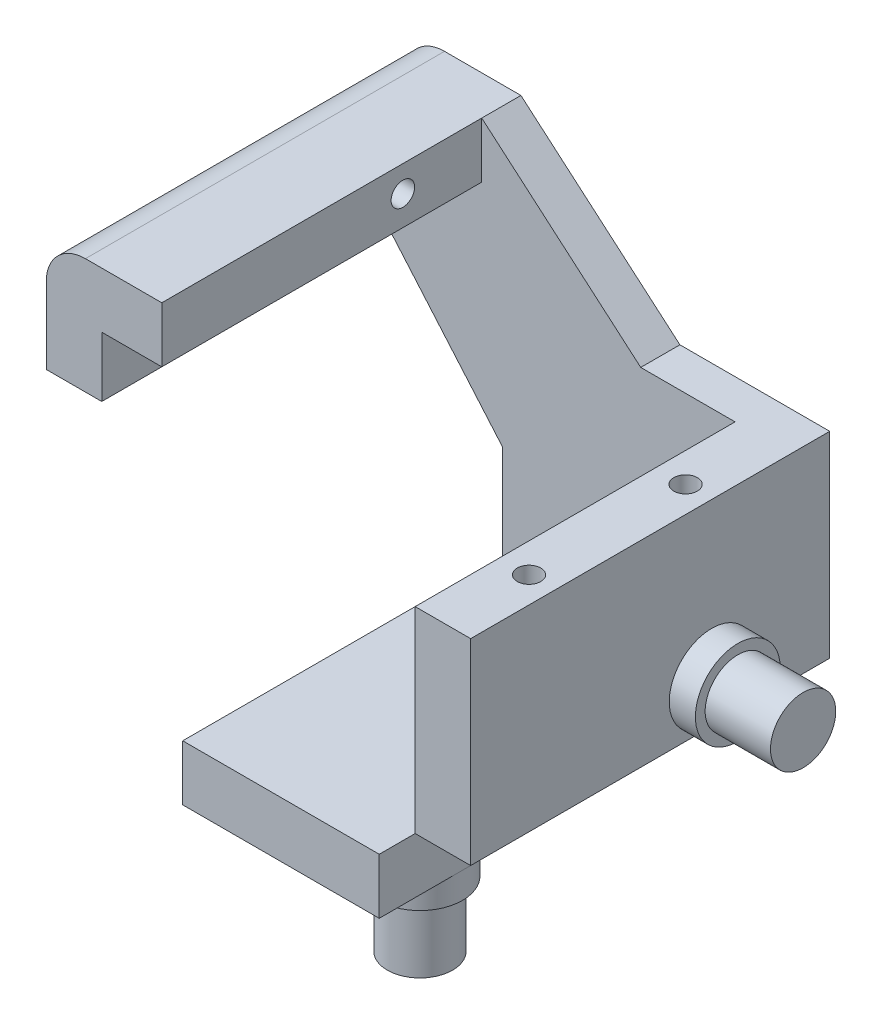
SolidWorks part; units mm, degrees
ref_plane "前视基准面" through (0, 0, 0) normal (0, 0, 1) x (1, 0, 0)
ref_plane "上视基准面" through (0, 0, 0) normal (0, 1, 0) x (1, 0, 0)
ref_plane "右视基准面" through (0, 0, 0) normal (1, 0, 0) x (0, 0, -1)
sketch "草图1" plane through (0, 0, 0) normal (0, 0, 1) x (1, 0, 0)
  line L1 (-16.25, -16.25) -> (16.25, -16.25)
  line L2 (-16.25, -16.25) -> (-16.25, 13.25)
  line L3 (-13.25, 16.25) -> (16.25, 16.25)
  line L4 (16.25, -16.25) -> (16.25, 16.25)
  arc A0 (-13.25, 16.25) -> (-16.25, 13.25) centre (-13.25, 13.25) ccw
  dimension "D1" = 3
extrude "凸台-拉伸1" add sketch "草图1" along normal blind 27.5
sketch "草图3" plane through (0, 0, 27.5) normal (0, 0, 1) x (1, 0, 0)
  line L1 (-12, -12) -> (12, -12)
  line L2 (-12, -12) -> (-12, 12)
  line L3 (-12, 12) -> (12, 12)
  line L4 (12, -12) -> (12, 12)
extrude "切除-拉伸3" cut sketch "草图3" against normal blind 24.5
sketch "草图4" plane through (0, 0, 27.5) normal (0, 0, 1) x (1, 0, 0)
  line L0 (-16.25, 16.25) -> (16.25, -16.25)
  line L1 (16.25, 16.25) -> (-7.4, 16.25)
  line L2 (16.25, 16.25) -> (16.25, 5.8)
  line L3 (16.25, 5.8) -> (-0.175, 5.8)
  line L5 (-7.4, 16.25) -> (-7.4, 12)
  line L7 (12, 12) -> (-12, 12) construction
  line L8 (-7.4, 12) -> (-0.175, 5.8)
extrude "切除-拉伸4" cut sketch "草图4" along direction (0, 0, -1) on the side against the normal blind 24.5 contours L3 L8 L5 L1 L2
ref_plane "基准面3" through (0, 0, 0) normal (0.7071, 0.7071, 0) x (0.7071, -0.7071, 0)
mirror "镜向1" about plane through (0, 0, 0) normal (0.7071, 0.7071, 0) of "切除-拉伸4"
sketch "草图6" plane through (0, 0, 0) normal (0, 0, -1) x (-1, 0, 0)
  line L0 (10.695, 10.695) -> (-10.695, -10.695) construction
  line L1 (-16.25, -16.25) -> (-6, -16.25)
  line L2 (-16.25, -16.25) -> (-16.25, -6)
  line L3 (-16.25, -6) -> (-6, -6)
  line L4 (-6, -16.25) -> (-6, -6)
sketch "草图7" plane through (0, -16.25, 0) normal (0, -1, 0) x (1, 0, 0)
  line L0 (6, 0) -> (6, 21.13)
  circle A1 centre (6, 21.13) radius 3.25
  dimension "D1" = 21.13
  dimension "D2" = 6.5
extrude "凸台-拉伸4" add sketch "草图7" along normal blind 2 contours A1
sketch "草图10" plane through (16.25, 0, 0) normal (1, 0, 0) x (0, 0, -1)
  line L0 (0, -6) -> (-9.04, -6)
  line L1 (0, -16.25) -> (0, -6) construction
  line L2 (0, -16.25) -> (0, -6) construction
  circle A0 centre (-9.04, -6) radius 3.25
  dimension "D1" = 9.04
  dimension "D2" = 6.5
extrude "凸台-拉伸5" add sketch "草图10" along normal blind 2 contours A0
sketch "草图13" plane through (0, 0, 27.5) normal (0, 0, 1) x (1, 0, 0)
  line L1 (16.25, -16.25) -> (9.25, -16.25)
  line L2 (16.25, -16.25) -> (16.25, -9.25)
  line L3 (16.25, -9.25) -> (12, -9.25)
  line L4 (9.25, -16.25) -> (9.25, -12)
  arc A0 (12, -9.25) -> (9.25, -12) centre (12, -12) ccw
  dimension "D1" = 2.75
extrude "切除-拉伸6" cut sketch "草图13" against normal blind 27.5
sketch "草图14" plane through (0, 0, 3) normal (0, 0, 1) x (1, 0, 0)
  line L0 (16.25, 5.8) -> (4.7758, 5.8)
  line L1 (4.7758, 5.8) -> (-7.4, 16.25)
  line L2 (-7.4, 16.25) -> (16.25, 16.25)
  line L3 (16.25, 16.25) -> (16.25, 5.8)
extrude "切除-拉伸7" cut sketch "草图14" against normal blind 3
mirror "镜向3" about plane through (0, 0, 0) normal (0.7071, 0.7071, 0) of "切除-拉伸7"
sketch "草图16" plane through (0, 5.8, 0) normal (0, 1, 0) x (1, 0, 0)
  line L0 (16.25, 0) -> (14.25, 0)
  line L1 (4.7758, 0) -> (16.25, 0) construction
  line L2 (14.25, 0) -> (14.25, -9.04)
  line L3 (14.25, 0) -> (14.25, -21.03)
  circle A0 centre (14.25, -9.04) radius 0.9
  circle A1 centre (14.25, -21.03) radius 0.9
  dimension "D1" = 1.8
  dimension "D2" = 1.8
extrude "切除-拉伸10" cut sketch "草图16" against normal blind 6 contours A0 | A1
mirror "镜向4" about plane through (0, 0, 0) normal (0.7071, 0.7071, 0) of "切除-拉伸10"
sketch "草图17" plane through (-7.4, 0, 0) normal (1, 0, 0) x (0, 0, -1)
  line L0 (-27.5, 16.25) -> (-27.5, 14.25)
  line L1 (-27.5, 16.25) -> (-27.5, 12) construction
  line L2 (-27.5, 14.25) -> (-21.03, 14.25)
  line L3 (-27.5, 14.25) -> (-9.04, 14.25)
  circle A0 centre (-21.03, 14.25) radius 0.9
  circle A1 centre (-9.04, 14.25) radius 0.9
  dimension "D1" = 6.47
  dimension "D3" = 1.8
  dimension "D4" = 1.8
  dimension "D2" = 18.46
sketch "草图19" plane through (18.25, 0, 0) normal (1, 0, 0) x (0, 0, -1)
  circle A0 centre (-9.04, -6) radius 2.5
sketch "草图20" plane through (0, -18.25, 0) normal (0, -1, 0) x (1, 0, 0)
  circle A0 centre (6, 21.13) radius 2.5
extrude "凸台-拉伸6" add sketch "草图20" along normal blind 5 contours A0
extrude "凸台-拉伸7" add sketch "草图19" along normal blind 5 contours A0
extrude "切除-拉伸11" cut sketch "草图17" against normal blind 6 contours A1
sketch "草图21" plane through (0, 7.4, 0) normal (0, -1, 0) x (-1, 0, 0)
  line L1 (12, -3) -> (12, -27.5) construction
  line L2 (16.25, -27.5) -> (12, -27.5) construction
  circle A0 centre (14.25, -21.03) radius 0.9
  dimension "D1" = 2.25
  dimension "D2" = 6.47
extrude "切除-拉伸12" cut sketch "草图21" against normal blind 6 contours A0
